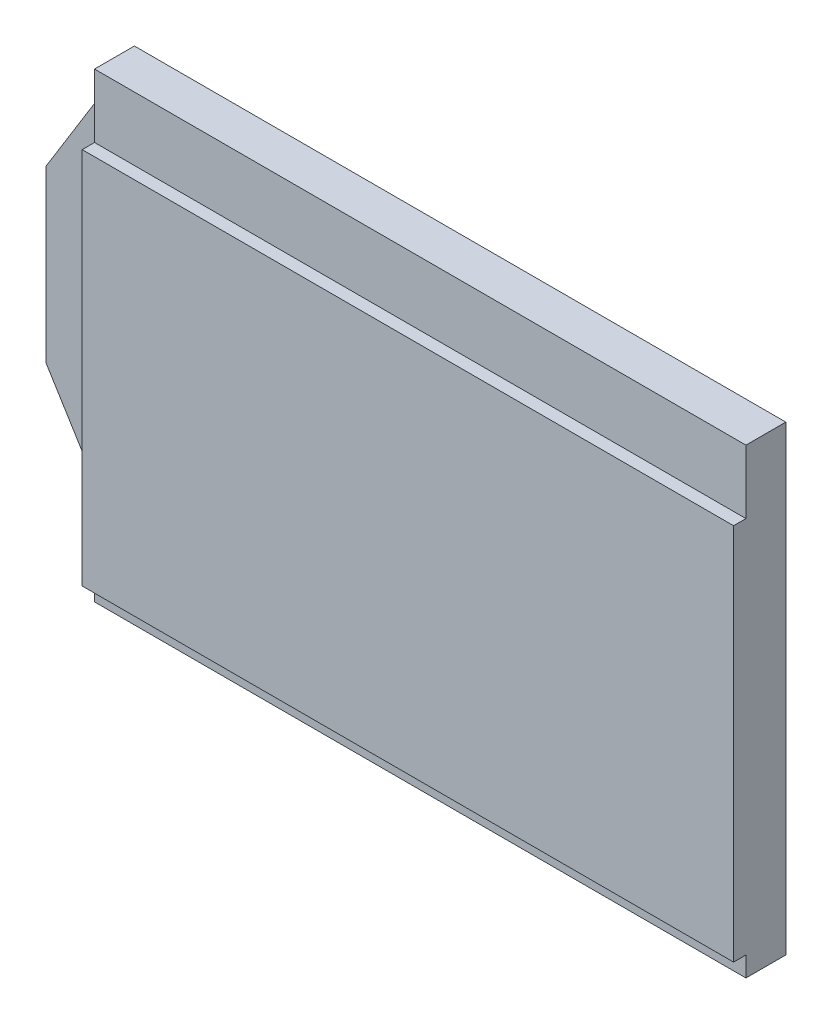
SolidWorks part; units mm, degrees
material "Szkło"
ref_plane "Płaszczyzna przednia" through (0, 0, 0) normal (0, 0, 1) x (1, 0, 0)
ref_plane "Płaszczyzna górna" through (0, 0, 0) normal (0, 1, 0) x (1, 0, 0)
ref_plane "Płaszczyzna prawa" through (0, 0, 0) normal (1, 0, 0) x (0, 0, -1)
sketch "Szkic1" plane through (0, 0, 0) normal (0, 0, 1) x (1, 0, 0)
  line L1 (-34.3, 24.3) -> (34.3, 24.3)
  line L2 (-34.3, 24.3) -> (-34.3, -24.3)
  line L3 (-34.3, -24.3) -> (34.3, -24.3)
  line L4 (34.3, 24.3) -> (34.3, -24.3)
  line L5 (-34.3, 24.3) -> (34.3, -24.3) construction
  line L6 (-34.3, -24.3) -> (34.3, 24.3) construction
  point P0 (0, 0)
  dimension "D1" = 68.6
  dimension "D2" = 48.6
extrude "Dodanie-wyciągnięcie1" add sketch "Szkic1" along normal blind 4.2
sketch "Szkic2" plane through (0, 0, 4.2) normal (0, 0, 1) x (1, 0, 0)
  line L1 (-34.3, -22.2) -> (34.3, -22.2)
  line L2 (-34.3, -22.2) -> (-34.3, 17.6)
  line L3 (-34.3, 17.6) -> (34.3, 17.6)
  line L4 (34.3, -22.2) -> (34.3, 17.6)
  line L6 (-34.3, -24.3) -> (34.3, -24.3) construction
  line L7 (34.3, -24.3) -> (34.3, 24.3) construction
  dimension "D1" = 68.6
  dimension "D2" = 39.8
  dimension "D3" = 2.1
extrude "Dodanie-wyciągnięcie2" add sketch "Szkic2" along normal blind 1.3
sketch "Szkic3" plane through (0, 0, 0) normal (0, 0, -1) x (-1, 0, 0)
  line L0 (-34.3, 24.3) -> (34.3, 24.3) construction
  line L1 (34.3, 22.2189) -> (41.0904, 11.2189)
  line L2 (34.3, 22.2189) -> (34.3, -17.7811)
  line L3 (34.3, -17.7811) -> (41.0904, -6.7811)
  line L4 (41.0904, 11.2189) -> (41.0904, -6.7811)
  line L6 (34.3, 24.3) -> (34.3, -24.3) construction
  point P5 (41.0904, 2.2189)
  point P6 (34.3, 2.2189)
  dimension "D1" = 18
  dimension "D2" = 40
  dimension "D3" = 2.0811
  dimension "D4" = 31.687
extrude "Dodanie-wyciągnięcie3" add sketch "Szkic3" against normal blind 2.5 separate body
